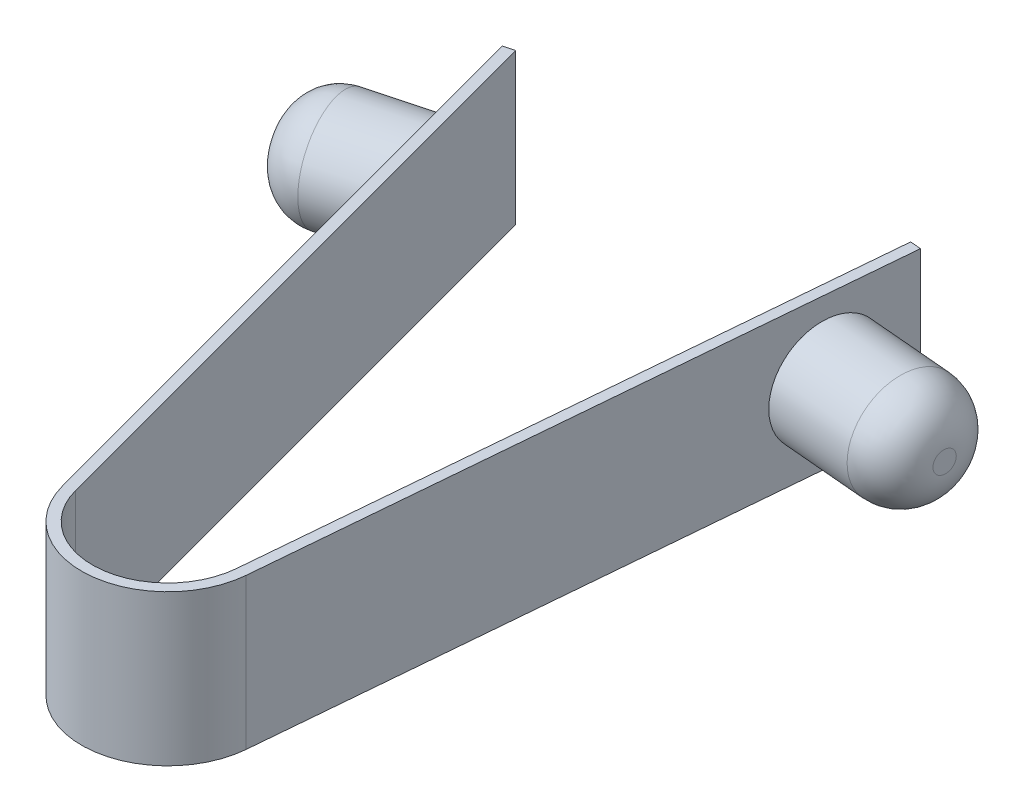
SolidWorks part; units mm, degrees
ref_plane "Front Plane" through (0, 0, 0) normal (0, 0, 1) x (1, 0, 0)
ref_plane "Top Plane" through (0, 0, 0) normal (0, 1, 0) x (1, 0, 0)
ref_plane "Right Plane" through (0, 0, 0) normal (1, 0, 0) x (0, 0, -1)
sketch "Sketch1" plane through (0, 0, 0) normal (0, 1, 0) x (1, 0, 0)
  line L0 (-6.1336, -1.6435) -> (-18.0058, 42.664)
  line L1 (6.3258, -0.5534) -> (10.3237, 45.1425)
  line L2 (0, 0) -> (0, 32.5891) construction
  line L3 (-6.1336, -6.35) -> (6.1336, -6.35) construction
  line L4 (-18.0058, 42.664) -> (-17.2391, 42.8694)
  line L5 (-17.2391, 42.8694) -> (-5.3669, -1.4381)
  line L6 (9.533, 45.2117) -> (5.5351, -0.4843)
  line L7 (9.533, 45.2117) -> (10.3237, 45.1425)
  line L8 (-4.9045, -2.6111) -> (-4.9045, -2.6111)
  line L9 (-4.9045, -2.6111) -> (-4.9045, -2.6111)
  line L10 (-4.9045, -2.6111) -> (-4.9045, -2.6111)
  line L11 (4.8637, -2.6863) -> (4.8637, -2.6863)
  line L12 (4.8637, -2.6863) -> (4.8637, -2.6863)
  line L13 (4.8637, -2.6863) -> (4.8637, -2.6863)
  line L14 (-17.2391, 42.8694) -> (-5.2448, -1.894) construction
  line L15 (9.533, 45.2117) -> (5.3941, -2.0958) construction
  arc A0 (-6.1336, -1.6435) -> (6.3258, -0.5534) centre (0, 0) ccw
  arc A1 (-5.3669, -1.4381) -> (5.5351, -0.4843) centre (0, 0) ccw
  arc A2 (-4.9045, -2.6111) -> (4.8637, -2.6863) centre (0, 0) ccw construction
  point P10 (0.5534, -6.3258)
  dimension "D1" = 12.7
  dimension "D2" = 20
  dimension "D3" = 15
  dimension "D4" = 52.3875
  dimension "D5" = 0.7937
  dimension "D6" = 0.7937
  dimension "D7" = 0.7937
extrude "Boss-Extrude1" add sketch "Sketch1" along normal blind 11.1125 contours L1 L7 L6 A1 L5 L4 L0 A0
sketch "Sketch2" plane through (6.3258, 0, 0.5534) normal (0.9962, 0, 0.0872) x (0.0872, 0, -0.9962)
  line L0 (0, 5.5562) -> (45.8705, 5.5562) construction
  line L1 (0, 11.1125) -> (0, 0) construction
  line L2 (45.8705, 11.1125) -> (45.8705, 0) construction
  circle A0 centre (39.5205, 5.5562) radius 3.9687
  dimension "D1" = 7.9375
  dimension "D2" = 6.35
extrude "Boss-Extrude2" add sketch "Sketch2" along normal blind 9.525
sketch "Sketch4" plane through (-6.1336, 0, 1.6435) normal (-0.9659, 0, 0.2588) x (0.2588, 0, 0.9659)
  line L0 (-45.8705, 5.5562) -> (0, 5.5562) construction
  line L1 (-45.8705, 11.1125) -> (-45.8705, 0) construction
  line L2 (0, 11.1125) -> (0, 0) construction
  circle A0 centre (-39.5205, 5.5562) radius 3.9687
  dimension "D1" = 7.9375
  dimension "D2" = 6.35
extrude "Boss-Extrude3" add sketch "Sketch4" along normal blind 9.525
fillet "Fillet1" radius 3.175 2 edges at (19.6049, 5.5562, -41.9402) (-24.5355, 5.5562, -30.2316)
